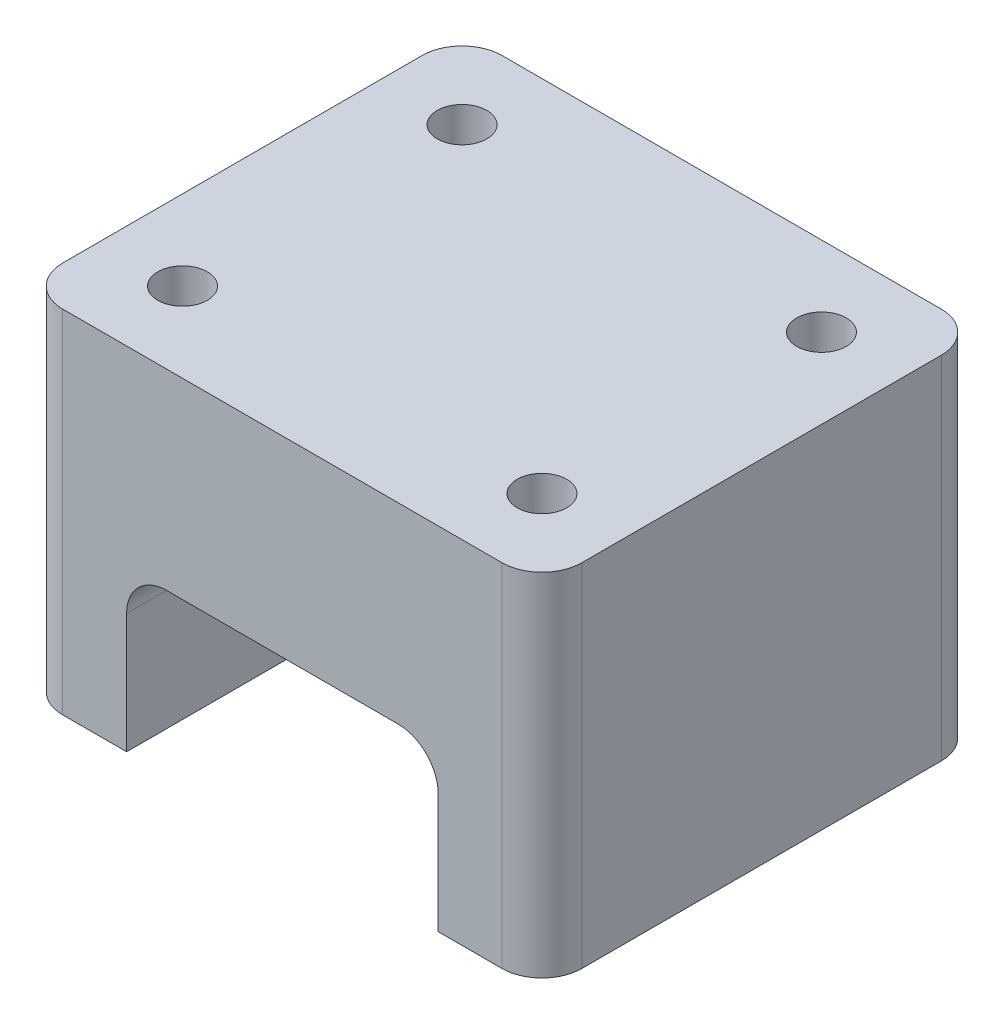
SolidWorks part; units mm, degrees
material "ABS"
ref_plane "Front Plane" through (0, 0, 0) normal (0, 0, 1) x (1, 0, 0)
ref_plane "Top Plane" through (0, 0, 0) normal (0, 1, 0) x (1, 0, 0)
ref_plane "Right Plane" through (0, 0, 0) normal (1, 0, 0) x (0, 0, -1)
sketch "Sketch1" plane through (0, 0, 0) normal (0, 1, 0) x (1, 0, 0)
  line L1 (0, 0) -> (65, 0)
  line L2 (0, 0) -> (0, 55)
  line L3 (0, 55) -> (65, 55)
  line L4 (65, 0) -> (65, 55)
  dimension "D1" = 65
  dimension "D2" = 55
extrude "Boss-Extrude1" add sketch "Sketch1" along normal blind 44
sketch "Sketch2" plane through (0, 0, 0) normal (0, 0, 1) x (1, 0, 0)
  line L0 (0, 0) -> (65, 0) construction
  line L1 (52, 0) -> (13, 0)
  line L2 (52, 0) -> (52, 20)
  line L3 (52, 20) -> (13, 20)
  line L4 (13, 0) -> (13, 20)
  line L6 (65, 44) -> (65, 0) construction
  line L7 (0, 44) -> (0, 0) construction
  dimension "D1" = 20
  dimension "D2" = 13
  dimension "D3" = 13
extrude "Cut-Extrude1" cut sketch "Sketch2" against normal through all
fillet "Fillet1" radius 5 2 edges at (13, 20, -27.5) (52, 20, -27.5)
sketch "Sketch3" plane through (0, 0, 0) normal (0, -1, 0) x (1, 0, 0)
  line L0 (0, 0) -> (13, 0) construction
  line L1 (0, -55) -> (0, 0) construction
  line L2 (65, -55) -> (52, -55) construction
  line L3 (65, 0) -> (65, -55) construction
  circle A0 centre (58.5, -6.5) radius 3.1
  circle A1 centre (58.5, -48.5) radius 3.1
  circle A2 centre (6.5, -48.5) radius 3.1
  circle A3 centre (6.5, -6.5) radius 3.1
  dimension "D1" = 6.2
  dimension "D2" = 6.2
  dimension "D3" = 6.2
  dimension "D4" = 6.2
  dimension "D5" = 6.5
  dimension "D6" = 6.5
  dimension "D7" = 6.5
  dimension "D8" = 6.5
extrude "Cut-Extrude2" cut sketch "Sketch3" against normal blind 8.5
sketch "Sketch4" plane through (0, 44, 0) normal (0, 1, 0) x (1, 0, 0)
  line L0 (0, 55) -> (0, 0) construction
  line L1 (65, 55) -> (0, 55) construction
  circle A0 centre (10, 45) radius 3.1
  circle A1 centre (55, 45) radius 3.1
  circle A2 centre (55, 10) radius 3.1
  circle A3 centre (10, 10) radius 3.1
  dimension "D1" = 6.2
  dimension "D2" = 10
  dimension "D3" = 10
  dimension "D4" = 2
  dimension "D5" = 2
extrude "Cut-Extrude3" cut sketch "Sketch4" against normal blind 10
fillet "Fillet2" radius 5 4 edges at (65, 22, 0) (0, 22, 0) (0, 22, -55) (65, 22, -55)
